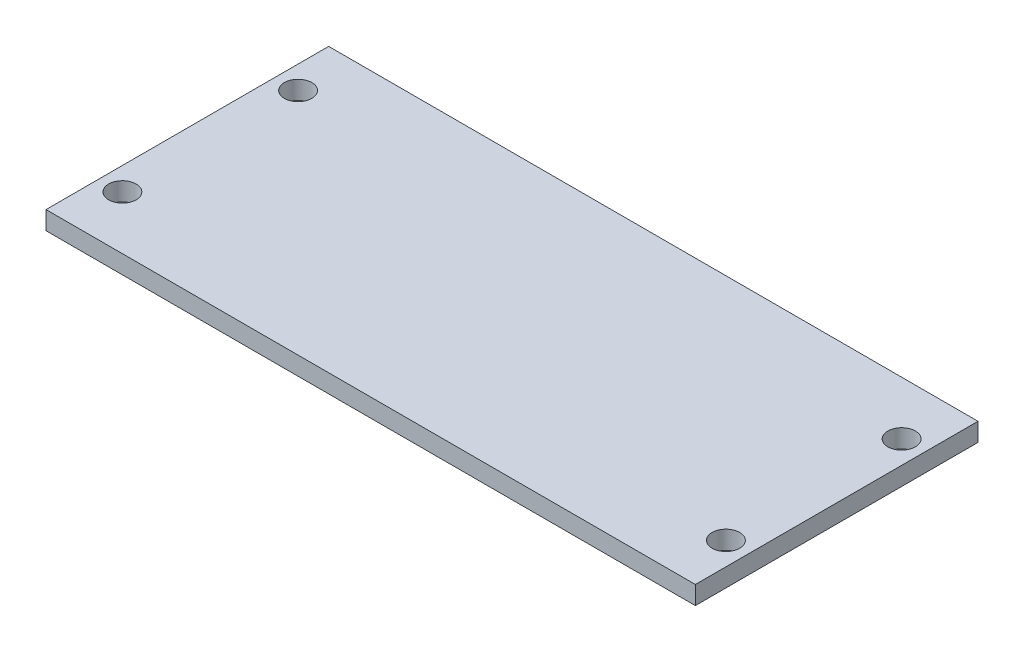
SolidWorks part; units mm, degrees
ref_plane "Front Plane" through (0, 0, 0) normal (0, 0, 1) x (1, 0, 0)
ref_plane "Top Plane" through (0, 0, 0) normal (0, 1, 0) x (1, 0, 0)
ref_plane "Right Plane" through (0, 0, 0) normal (1, 0, 0) x (0, 0, -1)
sketch "Sketch3" plane through (0, 0, 0) normal (0, 1, 0) x (1, 0, 0)
  line L0 (0, 92.5) -> (0, -92.5) construction
  line L1 (-212.5, -92.5) -> (212.5, -92.5)
  line L2 (-212.5, -92.5) -> (-212.5, 92.5)
  line L3 (-212.5, 92.5) -> (212.5, 92.5)
  line L4 (212.5, -92.5) -> (212.5, 92.5)
  line L5 (-212.5, -92.5) -> (212.5, 92.5) construction
  line L6 (-212.5, 92.5) -> (212.5, -92.5) construction
  circle A0 centre (-197.5, 57.5) radius 9
  circle A1 centre (-197.5, -57.5) radius 9
  circle A2 centre (197.5, 57.5) radius 9
  circle A3 centre (197.5, -57.5) radius 9
  point P0 (0, 0)
  dimension "D3" = 35
  dimension "D4" = 15
  dimension "D5" = 18
  dimension "D8" = 18
  dimension "D1" = 425
  dimension "D2" = 185
  dimension "D6" = 15
  dimension "D7" = 35
extrude "Boss-Extrude1" add sketch "Sketch3" along normal blind 12
